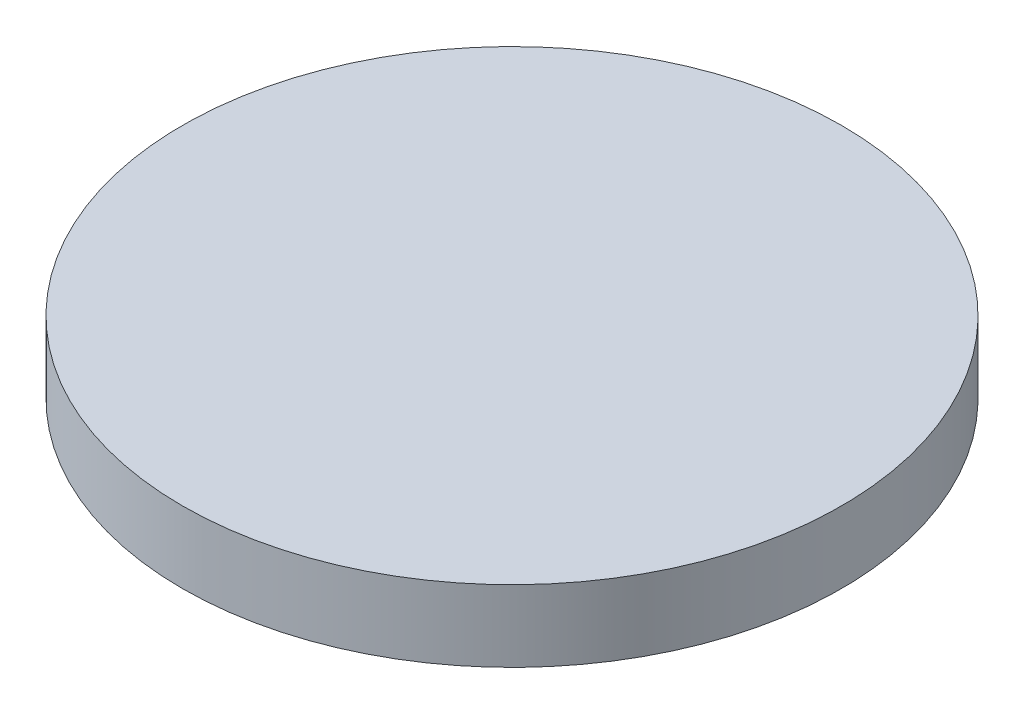
SolidWorks part; units mm, degrees
ref_plane "Plano frontal" through (0, 0, 0) normal (0, 0, 1) x (1, 0, 0)
ref_plane "Plano superior" through (0, 0, 0) normal (0, 1, 0) x (1, 0, 0)
ref_plane "Plano direito" through (0, 0, 0) normal (1, 0, 0) x (0, 0, -1)
sketch "Esboço1" plane through (0, 0, 0) normal (0, 1, 0) x (1, 0, 0)
  circle A0 centre (0, 0) radius 23
  dimension "D1" = 46
extrude "Ressalto-extrusão1" add sketch "Esboço1" along normal blind 5
